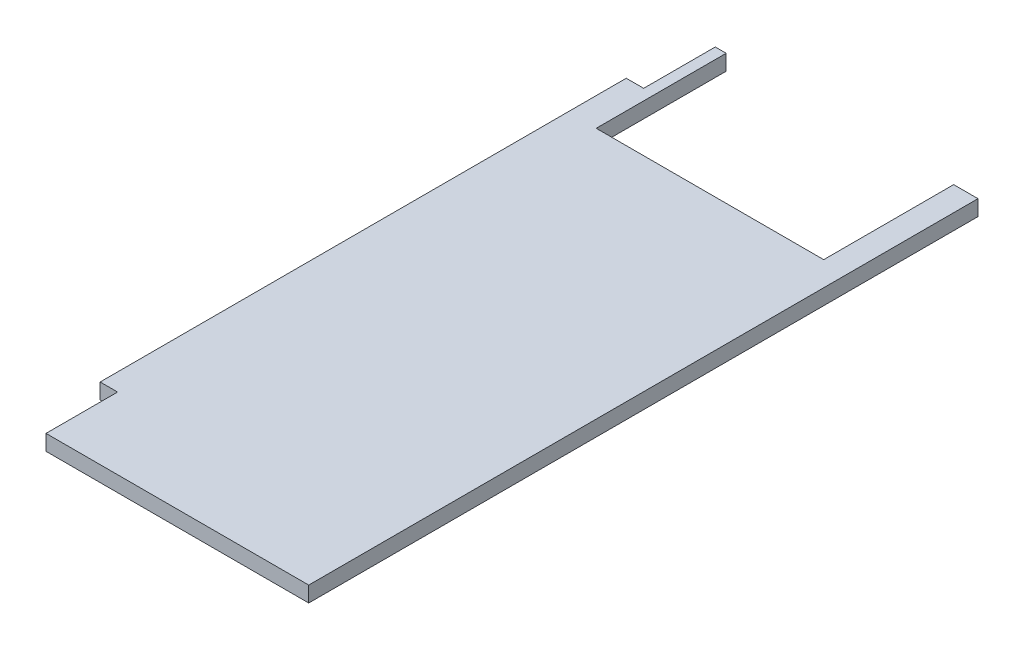
SolidWorks part; units mm, degrees
material "Balsa"
ref_plane "Plan de face" through (0, 0, 0) normal (0, 0, 1) x (1, 0, 0)
ref_plane "Plan de dessus" through (0, 0, 0) normal (0, 1, 0) x (1, 0, 0)
ref_plane "Plan de droite" through (0, 0, 0) normal (1, 0, 0) x (0, 0, -1)
sketch "Esquisse1" plane through (0, 0, 0) normal (0, 1, 0) x (1, 0, 0)
  line L1 (0, 0) -> (-180, 0)
  line L2 (0, 0) -> (0, 430)
  line L3 (0, 430) -> (-180, 430)
  line L4 (-180, 0) -> (-180, 430)
  dimension "D1" = 180
  dimension "D2" = 430
extrude "Boss.-Extru.1" add sketch "Esquisse1" along normal blind 10
sketch "Esquisse2" plane through (0, 10, 0) normal (0, 1, 0) x (1, 0, 0)
  line L0 (0, 430) -> (-180, 430) construction
  line L1 (-15.6278, 430) -> (-161.8, 430)
  line L2 (-15.6278, 430) -> (-15.6278, 346.5)
  line L3 (-15.6278, 346.5) -> (-161.8, 346.5)
  line L4 (-161.8, 430) -> (-161.8, 346.5)
extrude "Enlèv. mat.-Extru.1" cut sketch "Esquisse2" against normal blind 10
sketch "Esquisse3" plane through (0, 10, 0) normal (0, 1, 0) x (1, 0, 0)
  line L1 (-180, 430) -> (-168.8, 430)
  line L2 (-180, 430) -> (-180, 384)
  line L3 (-180, 384) -> (-168.8, 384)
  line L4 (-168.8, 430) -> (-168.8, 384)
  line L5 (-180, 0) -> (-168.8, 0)
  line L6 (-180, 0) -> (-180, 46)
  line L7 (-180, 46) -> (-168.8, 46)
  line L8 (-168.8, 0) -> (-168.8, 46)
  dimension "D1" = 46
  dimension "D2" = 11.2
  dimension "D3" = 46
  dimension "D4" = 11.2
extrude "Enlèv. mat.-Extru.2" cut sketch "Esquisse3" against normal blind 10
